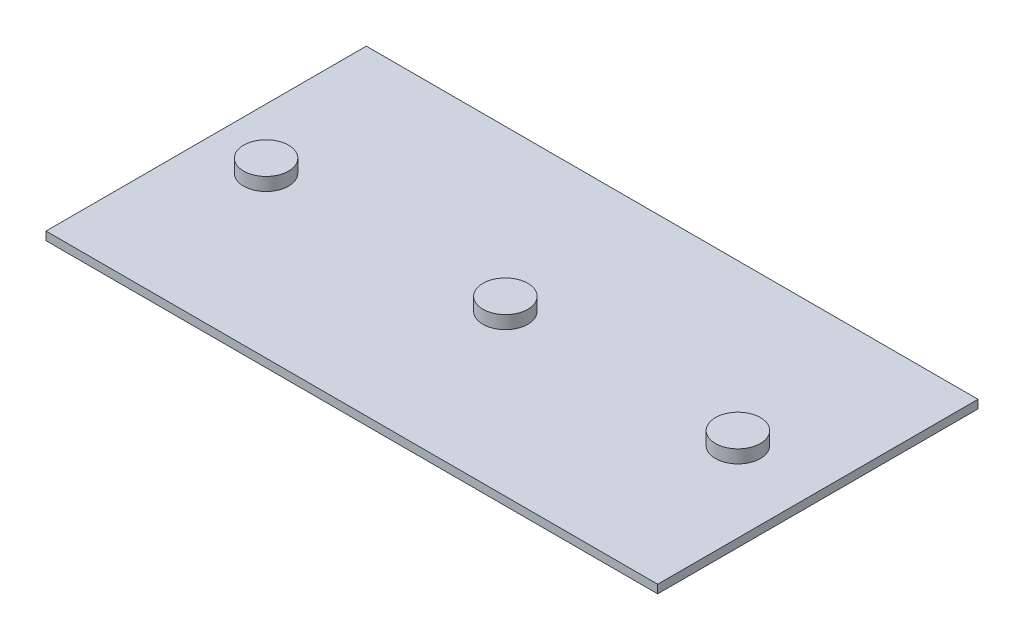
SolidWorks part; units mm, degrees
material "AISI 1020"
ref_plane "Plan de face" through (0, 0, 0) normal (0, 0, 1) x (1, 0, 0)
ref_plane "Plan de dessus" through (0, 0, 0) normal (0, 1, 0) x (1, 0, 0)
ref_plane "Plan de droite" through (0, 0, 0) normal (1, 0, 0) x (0, 0, -1)
sketch "Esquisse1" plane through (0, 0, 0) normal (0, 1, 0) x (1, 0, 0)
  line L1 (0, 0) -> (117.07, 0)
  line L2 (0, 0) -> (0, -61.3)
  line L3 (0, -61.3) -> (117.07, -61.3)
  line L4 (117.07, 0) -> (117.07, -61.3)
  dimension "D1" = 117.07
  dimension "D2" = 61.3
extrude "Boss.-Extru.1" add sketch "Esquisse1" along normal blind 1.6
sketch "Esquisse2" plane through (0, 0, 0) normal (0, -1, 0) x (1, 0, 0)
  line L0 (55, 0) -> (-55, 0) construction
  line L1 (94.07, 38.6) -> (109.07, 38.6)
  line L2 (94.07, 38.6) -> (94.07, 23)
  line L3 (94.07, 23) -> (109.07, 23)
  line L4 (109.07, 38.6) -> (109.07, 23)
  line L5 (117.07, 61.3) -> (117.07, 0) construction
  dimension "D1" = 15.6
  dimension "D2" = 23
  dimension "D3" = 8
  dimension "D4" = 15
extrude "Boss.-Extru.2" add sketch "Esquisse2" along normal blind 4
sketch "Esquisse3" plane through (0, 1.6, 0) normal (0, 1, 0) x (1, 0, 0)
  line L0 (19.2215, -30.65) -> (110.6537, -30.65) construction
  line L3 (117.07, 0) -> (117.07, -61.3) construction
  line L4 (0, -61.3) -> (117.07, -61.3) construction
  line L7 (-3.08, 0) -> (3.08, 0) construction
  line L8 (117.07, -61.3) -> (117.07, 0) construction
  circle A0 centre (101.77, -30.65) radius 4.3
  circle A1 centre (57.27, -30.65) radius 4.3
  circle A2 centre (11.47, -30.65) radius 4.3
  point P10 (0, 0)
  point P15 (117.07, -30.65)
  dimension "D1" = 8.6
  dimension "D2" = 59.8
  dimension "D3" = 15.3
  dimension "D4" = 105.6
  dimension "D5" = 30.65
extrude "Boss.-Extru.3" add sketch "Esquisse3" along normal blind 2.5
